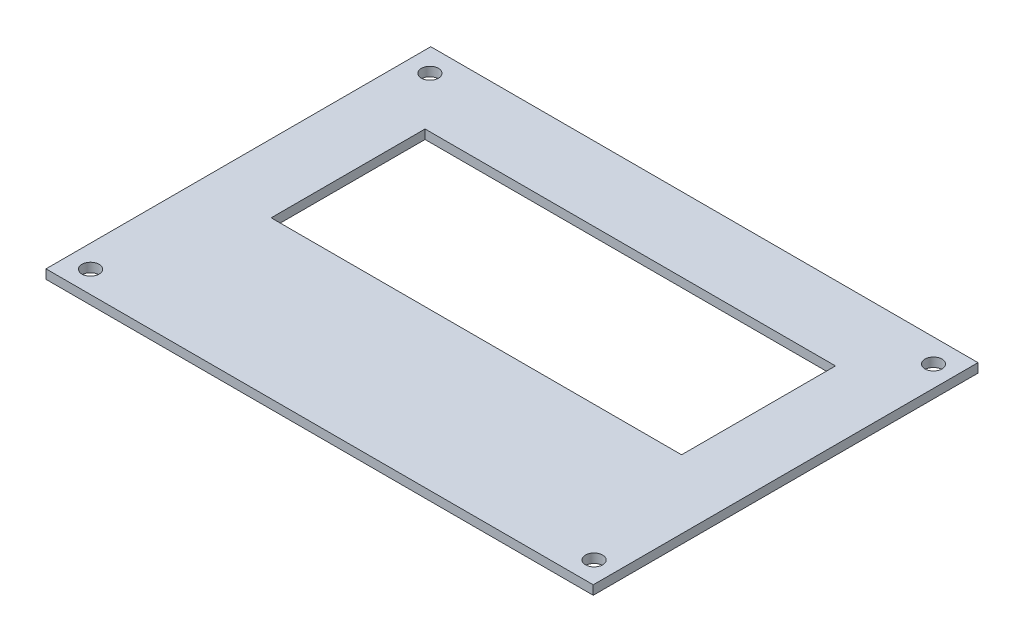
SolidWorks part; units mm, degrees
material "A-Glass Fiber"
ref_plane "Front Plane" through (0, 0, 0) normal (0, 0, 1) x (1, 0, 0)
ref_plane "Top Plane" through (0, 0, 0) normal (0, 1, 0) x (1, 0, 0)
ref_plane "Right Plane" through (0, 0, 0) normal (1, 0, 0) x (0, 0, -1)
sketch "Sketch1" plane through (0, 0, 0) normal (0, 1, 0) x (1, 0, 0)
  line L9 (0, 0) -> (96, 0)
  line L10 (0, 0) -> (0, 67.5)
  line L11 (0, 67.5) -> (96, 67.5)
  line L12 (96, 0) -> (96, 67.5)
  point P4 (0, 0)
  dimension "D1" = 96
  dimension "D2" = 67.5
extrude "Boss-Extrude1" add sketch "Sketch1" along normal blind 1.6 contours L9 L12 L11 L10
sketch "Sketch2" plane through (0, 1.6, 0) normal (0, 1, 0) x (1, 0, 0)
  line L0 (0, 0) -> (0, 67.5) construction
  line L1 (0, 0) -> (96, 0) construction
  circle A0 centre (3.96, 3.85) radius 1.5
  circle A1 centre (92.3, 3.85) radius 1.5
  circle A2 centre (3.96, 63.39) radius 1.5
  circle A3 centre (92.3, 63.39) radius 1.5
  point P6 (0, 0)
  point P9 (46.9158, 4.4202)
  point P10 (91.625, 3.85)
  point P13 (3.96, 63.0684)
  point P16 (91.625, 63.0684)
  point P17 (0, 0)
  point P18 (0, 0)
  point P19 (0, 0)
  dimension "D1" = 3
  dimension "D2" = 3.96
  dimension "D3" = 3.85
  dimension "D4" = 3.85
  dimension "D5" = 3.96
  dimension "D6" = 63.39
  dimension "D7" = 92.3
extrude "Cut-Extrude1" cut sketch "Sketch2" against normal up to next
sketch "Sketch3" plane through (0, 1.6, 0) normal (0, 1, 0) x (1, 0, 0)
  line L0 (0, 67.5) -> (96, 67.5) construction
  line L1 (12, 54.5) -> (84, 54.5)
  line L2 (12, 54.5) -> (12, 27.5)
  line L3 (12, 27.5) -> (84, 27.5)
  line L4 (84, 54.5) -> (84, 27.5)
  line L5 (0, 0) -> (96, 0) construction
  point P4 (48, 54.5)
  point P7 (48, 67.5)
  dimension "D1" = 27
  dimension "D2" = 72
  dimension "D3" = 27.5
extrude "Cut-Extrude2" cut sketch "Sketch3" against normal through all both and the other way through all
